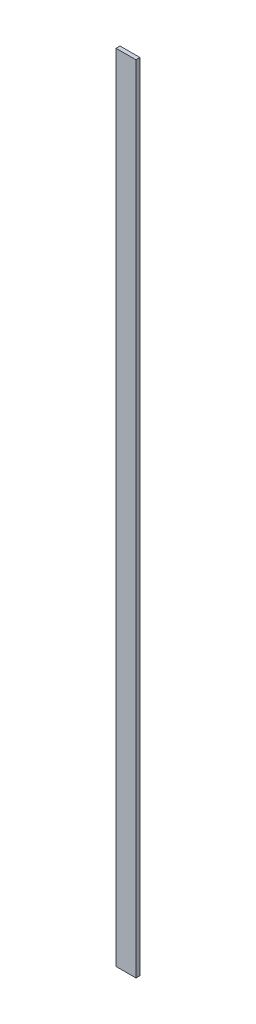
SolidWorks part; units mm, degrees
material "ASTM A36 Steel"
ref_plane "Front Plane" through (0, 0, 0) normal (0, 0, 1) x (1, 0, 0)
ref_plane "Top Plane" through (0, 0, 0) normal (0, 1, 0) x (1, 0, 0)
ref_plane "Right Plane" through (0, 0, 0) normal (1, 0, 0) x (0, 0, -1)
sketch "Sketch1" plane through (0, 0, 0) normal (0, 0, 1) x (1, 0, 0)
  line L1 (12.5, -500) -> (-12.5, -500)
  line L2 (12.5, -500) -> (12.5, 500)
  line L3 (12.5, 500) -> (-12.5, 500)
  line L4 (-12.5, -500) -> (-12.5, 500)
  line L5 (12.5, -500) -> (-12.5, 500) construction
  line L6 (12.5, 500) -> (-12.5, -500) construction
  point P0 (0, 0)
  dimension "D1" = 25
  dimension "D2" = 1000
extrude "Boss-Extrude1" add sketch "Sketch1" along normal mid plane 5
